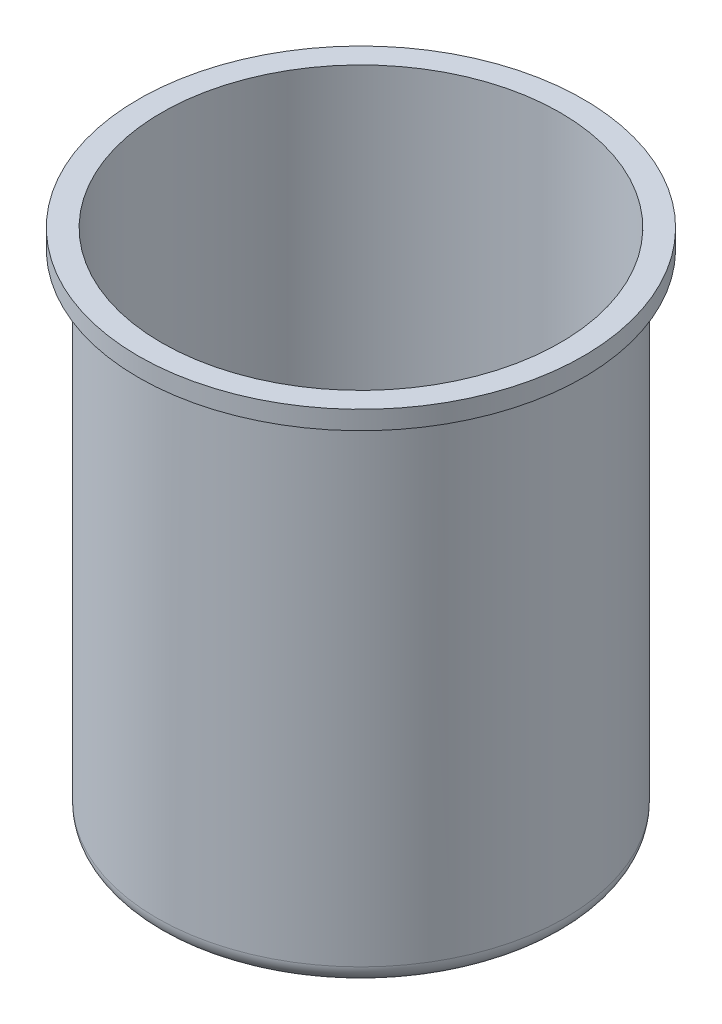
SolidWorks part; units mm, degrees
ref_plane "Front Plane" through (0, 0, 0) normal (0, 0, 1) x (1, 0, 0)
ref_plane "Top Plane" through (0, 0, 0) normal (0, 1, 0) x (1, 0, 0)
ref_plane "Right Plane" through (0, 0, 0) normal (1, 0, 0) x (0, 0, -1)
sketch "Sketch1" plane through (0, 0, 0) normal (0, 1, 0) x (1, 0, 0)
  circle A0 centre (0, 0) radius 279.4
  point P3 (0, 0)
extrude "Boss-Extrude3" add sketch "Sketch1" along normal blind 12.7
sketch "Sketch2" plane through (0, 12.7, 0) normal (0, 1, 0) x (1, 0, 0)
  circle A0 centre (0, 0) radius 273.05
  circle A3 centre (0, 0) radius 279.4
extrude "Boss-Extrude6" add sketch "Sketch2" along normal blind 692.15 contours A3
sketch "Sketch8" plane through (0, 704.85, 0) normal (0, 1, 0) x (1, 0, 0)
  circle A0 centre (0, 0) radius 273.05
extrude "Boss-Extrude7" add sketch "Sketch8" against normal blind 623.57
sketch "Sketch10" plane through (0, 704.85, 0) normal (0, 1, 0) x (1, 0, 0)
  circle A0 centre (0, 0) radius 273.05
extrude "Cut-Extrude1" cut sketch "Sketch10" against normal blind 623.57
fillet "Fillet1" radius 25.4 1 edges at (0, 0, 279.4)
fillet "Fillet2" radius 2.54 2 edges at (0, 704.85, 273.05) (0, 704.85, 279.4)
sketch "Sketch11" plane through (0, 704.85, 0) normal (0, 1, 0) x (1, 0, 0)
  circle A0 centre (0, 0) radius 304.8
extrude "Boss-Extrude8" add sketch "Sketch11" against normal blind 25.4
sketch "Sketch12" plane through (0, 704.85, 0) normal (0, 1, 0) x (1, 0, 0)
  circle A0 centre (0, 0) radius 273.05
extrude "Cut-Extrude6" cut sketch "Sketch12" against normal blind 25.4
sketch "Sketch13" plane through (0, 679.45, 0) normal (0, -1, 0) x (-1, 0, 0)
  circle A0 centre (0, 0) radius 292.1
  circle A1 centre (0, 0) radius 279.4
extrude "Cut-Extrude11" cut sketch "Sketch13" against normal blind 12.7
